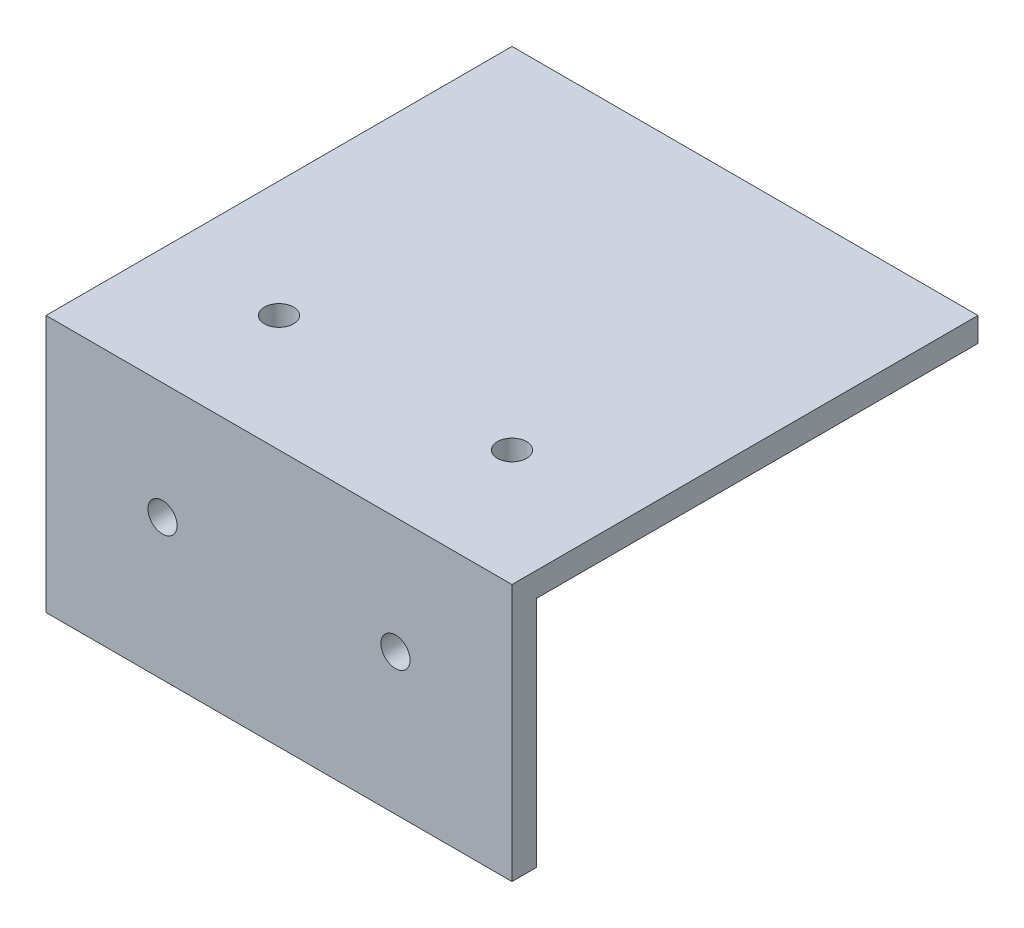
SolidWorks part; units mm, degrees
ref_plane "Front Plane" through (0, 0, 0) normal (0, 0, 1) x (1, 0, 0)
ref_plane "Top Plane" through (0, 0, 0) normal (0, 1, 0) x (1, 0, 0)
ref_plane "Right Plane" through (0, 0, 0) normal (1, 0, 0) x (0, 0, -1)
sketch "Sketch3" plane through (0, 0, 0) normal (0, 1, 0) x (1, 0, 0)
  line L1 (0, 0) -> (60.96, 0)
  line L2 (0, 0) -> (0, 60.96)
  line L3 (0, 60.96) -> (60.96, 60.96)
  line L4 (60.96, 0) -> (60.96, 60.96)
  dimension "D1" = 60.96
  dimension "D2" = 60.96
extrude "Boss-Extrude1" add sketch "Sketch3" along normal blind 3.175
hole_wizard "#6 (0.15) Diameter Hole1" positions "Sketch4" profile "Sketch5" hole size "#6" standard "ANSI Inch" end condition through all
sketch "Sketch4" plane through (0, 3.175, 0) normal (0, 1, 0) x (1, 0, 0)
  line L0 (0, 60.96) -> (0, 0) construction
  line L1 (0, 0) -> (60.96, 0) construction
  line L2 (60.96, 0) -> (60.96, 60.96) construction
  point P0 (15.24, 15.24)
  point P2 (45.72, 15.24)
  dimension "D1" = 15.24
  dimension "D2" = 15.24
  dimension "D3" = 15.24
  dimension "D4" = 15.24
sketch "Sketch5" plane through (15.24, 3.175, -15.24) normal (1, 0, 0) x (0, 0, 1)
  line L0 (0, 0) -> (0, 3.175)
  line L1 (0, 3.175) -> (1.905, 3.175)
  line L2 (1.905, 3.175) -> (1.905, 0)
  line L5 (1.905, 0) -> (0, 0)
  line L11 (0, -6.35) -> (0, 107.95) construction
  dimension "Thru Hole Dia." = 3.81
  dimension "Thru Hole Depth" = 3.175
sketch "Sketch6" plane through (0, 0, 0) normal (0, -1, 0) x (1, 0, 0)
  line L0 (60.96, 0) -> (60.96, -60.96) construction
  line L1 (0, 0) -> (60.96, 0)
  line L2 (0, 0) -> (0, -3.175)
  line L3 (0, -3.175) -> (60.96, -3.175)
  line L4 (60.96, 0) -> (60.96, -3.175)
  dimension "D1" = 3.175
extrude "Boss-Extrude3" add sketch "Sketch6" along normal blind 30.48
hole_wizard "#6 (0.15) Diameter Hole2" positions "Sketch7" profile "Sketch8" hole size "#6" standard "ANSI Inch" end condition through all
sketch "Sketch7" plane through (0, 0, 0) normal (0, 0, 1) x (1, 0, 0)
  line L0 (0, 3.175) -> (0, -30.48) construction
  line L1 (0, 3.175) -> (60.96, 3.175) construction
  line L2 (60.96, 3.175) -> (60.96, -30.48) construction
  point P0 (15.24, -12.065)
  point P2 (45.72, -12.065)
  dimension "D1" = 15.24
  dimension "D2" = 15.24
  dimension "D3" = 15.24
  dimension "D4" = 15.24
sketch "Sketch8" plane through (15.24, -12.065, 0) normal (1, 0, 0) x (0, -1, 0)
  line L0 (0, 0) -> (0, 60.96)
  line L1 (0, 60.96) -> (1.905, 60.96)
  line L2 (1.905, 60.96) -> (1.905, 0)
  line L5 (1.905, 0) -> (0, 0)
  line L11 (0, -6.35) -> (0, 107.95) construction
  dimension "Thru Hole Dia." = 3.81
  dimension "Thru Hole Depth" = 60.96
